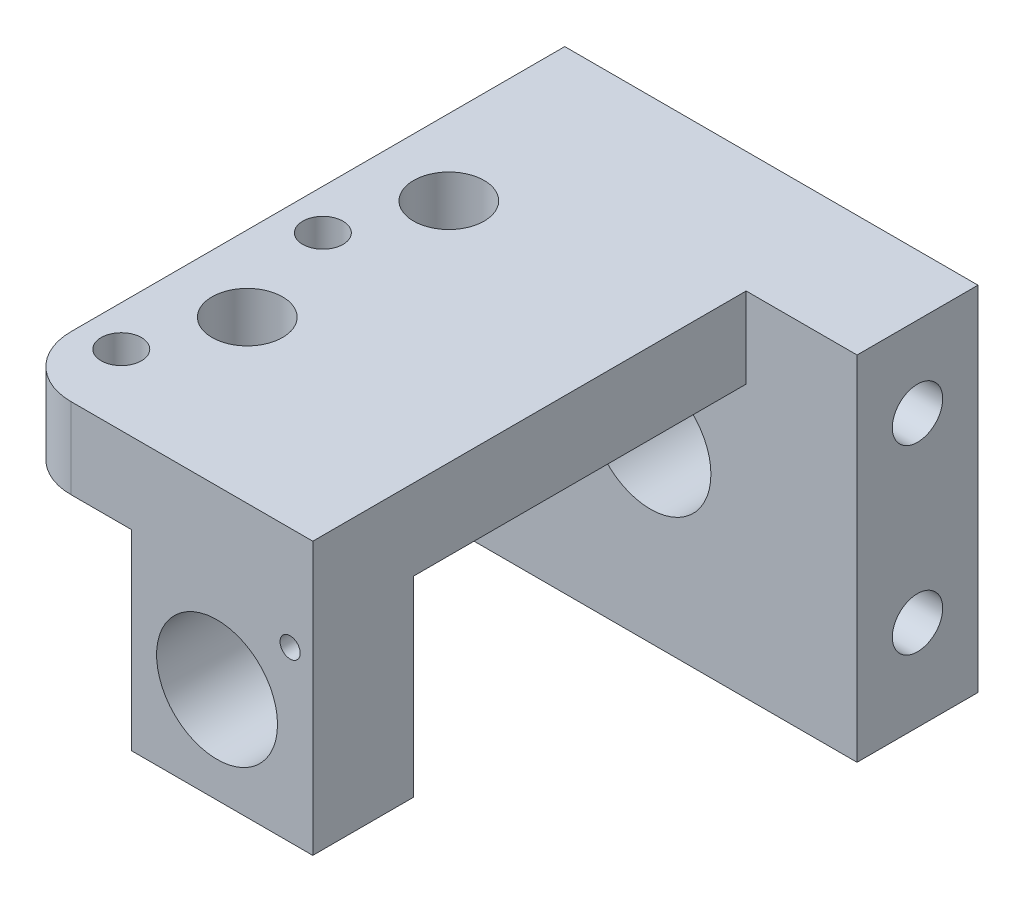
SolidWorks part; units mm, degrees
ref_plane "前视基准面" through (0, 0, 0) normal (0, 0, 1) x (1, 0, 0)
ref_plane "上视基准面" through (0, 0, 0) normal (0, 1, 0) x (1, 0, 0)
ref_plane "右视基准面" through (0, 0, 0) normal (1, 0, 0) x (0, 0, -1)
sketch "草图1" plane through (0, 0, 0) normal (0, 0, 1) x (1, 0, 0)
  line L1 (-20.5, -17.5) -> (20.5, -17.5)
  line L2 (-20.5, -17.5) -> (-20.5, 17.5)
  line L3 (-20.5, 17.5) -> (20.5, 17.5)
  line L4 (20.5, -17.5) -> (20.5, 17.5)
  line L5 (-20.5, -17.5) -> (20.5, 17.5) construction
  line L6 (-20.5, 17.5) -> (20.5, -17.5) construction
  point P0 (0, 0)
  dimension "D1" = 35
  dimension "D2" = 41
extrude "凸台-拉伸1" add sketch "草图1" along normal blind 12
sketch "草图2" plane through (0, 17.5, 0) normal (0, 1, 0) x (1, 0, 0)
  line L0 (-19.25, 0) -> (19.25, 0) construction
  line L1 (-20.5, 0) -> (9.5, 0)
  line L2 (-20.5, 0) -> (-20.5, -55)
  line L3 (-20.5, -55) -> (9.5, -55)
  line L4 (9.5, 0) -> (9.5, -55)
  line L5 (-20.5, -12) -> (-20.5, 0) construction
  dimension "D1" = 55
  dimension "D2" = 30
extrude "凸台-拉伸2" add sketch "草图2" against normal blind 8
sketch "草图3" plane through (0, 0, 55) normal (0, 0, 1) x (1, 0, 0)
  line L0 (-20.5, 17.5) -> (9.5, 17.5) construction
  line L1 (9.5, 9.5) -> (-8.5, 9.5)
  line L2 (9.5, 9.5) -> (9.5, -9.5)
  line L3 (9.5, -9.5) -> (-8.5, -9.5)
  line L4 (-8.5, 9.5) -> (-8.5, -9.5)
  line L5 (-20.5, 9.5) -> (-20.5, -17.5) construction
  dimension "D1" = 27
  dimension "D2" = 12
extrude "凸台-拉伸3" add sketch "草图3" against normal blind 10
fillet "圆角1" radius 6 1 edges at (-20.5, 13.5, 55)
sketch "草图5" plane through (0, 17.5, 0) normal (0, 1, 0) x (1, 0, 0)
  line L0 (-16.5, -48) -> (-16.5, -28) construction
  line L1 (-20.5, -49) -> (-20.5, 0) construction
  line L2 (-14.5, -55) -> (9.5, -55) construction
  point P0 (-16.5, -48)
  point P1 (-16.5, -28)
  dimension "D1" = 20
  dimension "D2" = 4
  dimension "D3" = 7
hole_wizard "Ø4.0mm 暗销孔1" positions "草图5" profile "草图6" hole size "Ø4.0" standard "GB" end condition through all
sketch "草图6" plane through (-16.5, 17.5, 48) normal (1, 0, 0) x (0, 0, 1)
  line L0 (0, 0) -> (0, 35)
  line L1 (0, 35) -> (2, 35)
  line L2 (2, 35) -> (2, 0)
  line L5 (2, 0) -> (0, 0)
  line L11 (0, -6.35) -> (0, 107.95) construction
  dimension "通孔孔直径" = 4
  dimension "通孔孔深度" = 35
sketch "草图7" plane through (0, 17.5, 0) normal (0, 1, 0) x (1, 0, 0)
  line L0 (-13, -39) -> (-13, -19) construction
  line L1 (-20.5, -49) -> (-20.5, 0) construction
  line L2 (-14.5, -55) -> (9.5, -55) construction
  point P0 (-13, -39)
  point P1 (-13, -19)
  dimension "D1" = 20
  dimension "D2" = 7.5
  dimension "D3" = 16
hole_wizard "Ø7.0 (7) 直径孔1" positions "草图7" profile "草图8" hole size "Ø7.0" standard "GB" end condition through all
sketch "草图8" plane through (-13, 17.5, 39) normal (1, 0, 0) x (0, 0, 1)
  line L0 (0, 0) -> (0, 8)
  line L1 (0, 8) -> (5.5, 8)
  line L2 (3.5, 6) -> (3.5, 0)
  line L5 (3.5, 0) -> (0, 0)
  line L7 (5.5, 8) -> (3.5, 6)
  line L8 (-5.5, 8) -> (-3.5, 6) construction
  line L11 (0, -6.35) -> (0, 107.95) construction
  dimension "通孔孔直径" = 7
  dimension "通孔孔深度" = 8
  dimension "远端锥形沉头孔直径" = 11
  dimension "远端锥形沉头孔角度" = 90
sketch "草图9" plane through (0, 0, 55) normal (0, 0, 1) x (1, 0, 0)
  line L1 (0, -19.25) -> (0, 19.25) construction
  line L2 (22.55, 0) -> (-22.55, 0) construction
  circle A0 centre (7.25, 7.25) radius 1
  dimension "D1" = 2
  dimension "D2" = 7.25
  dimension "D3" = 7.25
extrude "切除-拉伸1" cut sketch "草图9" against normal blind 10
hole_wizard "M6 螺纹孔1" positions "草图10" profile "草图11" tap size "M6" standard "GB"
sketch "草图10" plane through (20.5, 0, 0) normal (1, 0, 0) x (0, 0, -1)
  line L0 (-12, 17.5) -> (0, 17.5) construction
  line L1 (0, 19.25) -> (0, -19.25) construction
  point P0 (-6, 9.5)
  point P2 (-6, -8.5)
  dimension "D1" = 18
  dimension "D2" = 8
  dimension "D3" = 6
sketch "草图11" plane through (20.5, 9.5, 6) normal (0, 1, 0) x (0, 0, -1)
  line L0 (0, 0) -> (0, 13.5022)
  line L1 (0, 13.5022) -> (2.5, 12)
  line L2 (2.5, 12) -> (2.5, 0)
  line L5 (2.5, 0) -> (0, 0)
  line L10 (0, 13.5022) -> (-2.5, 12) construction
  line L11 (0, -6.35) -> (0, 107.95) construction
  dimension "螺纹孔钻头直径" = 5
  dimension "螺纹孔钻头深度" = 12
  dimension "导头角度" = 118
cosmetic thread "孔螺纹线1" parameters "D1"=10, "D2"=6
cosmetic thread "孔螺纹线2" parameters "D1"=10, "D2"=6
mirror "镜向1" about plane through (0, 0, 0) normal (1, 0, 0) of "M6 螺纹孔1"
cosmetic thread "孔螺纹线3" parameters "D1"=10, "D2"=6
cosmetic thread "孔螺纹线4" parameters "D1"=10, "D2"=6
sketch "草图12" plane through (0, 0, 55) normal (0, 0, 1) x (1, 0, 0)
  circle A0 centre (0, 0) radius 6
  dimension "D1" = 12
extrude "切除-拉伸2" cut sketch "草图12" against normal through all
